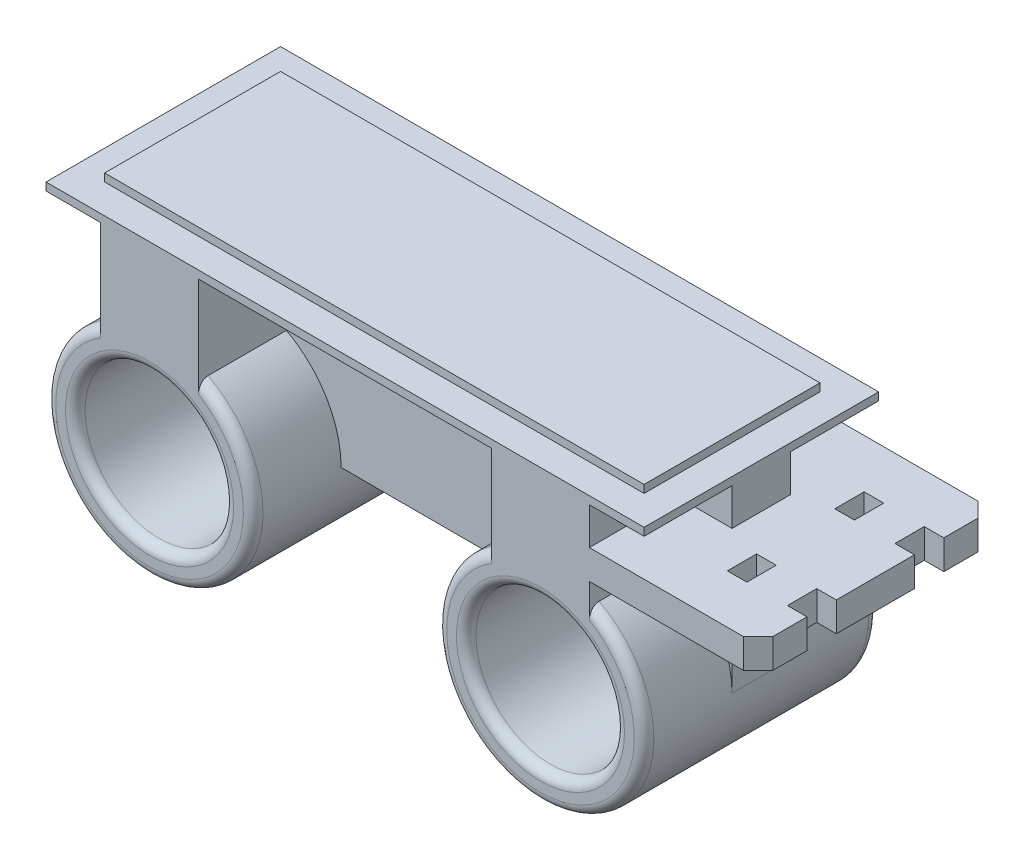
SolidWorks part; units mm, degrees
ref_plane "Plano frontal" through (0, 0, 0) normal (0, 0, 1) x (1, 0, 0)
ref_plane "Plano superior" through (0, 0, 0) normal (0, 1, 0) x (1, 0, 0)
ref_plane "Plano direito" through (0, 0, 0) normal (1, 0, 0) x (0, 0, -1)
sketch "Esboço1" plane through (0, 0, 0) normal (0, 0, 1) x (1, 0, 0)
  line L0 (-20, 0) -> (20, 0) construction
  circle A0 centre (-20, 0) radius 7.6
  circle A1 centre (-20, 0) radius 10.6
  circle A2 centre (20, 0) radius 10.6
  circle A3 centre (20, 0) radius 7.6
  point P2 (0, 0)
  dimension "D1" = 15.2
  dimension "D2" = 15.2
  dimension "D4" = 3
  dimension "D5" = 3
  dimension "D3" = 40
extrude "Ressalto-extrusão1" add sketch "Esboço1" along normal mid plane 24
fillet "Filete1" radius 1 4 edges at (-9.4, 0, -12) (-12.4, 0, -12) (-12.4, 0, 12) (-9.4, 0, 12)
fillet "Filete2" radius 1 4 edges at (27.6, 0, -12) (30.6, 0, -12) (30.6, 0, 12) (27.6, 0, 12)
sketch "Esboço2" plane through (0, 0, 0) normal (0, 0, 1) x (1, 0, 0)
  line L0 (-30.6, 0) -> (-30.6, 20)
  line L1 (-30.6, 20) -> (30.6, 20)
  line L2 (30.6, 0) -> (30.6, 20)
  line L3 (-9.4, 0) -> (9.4, 0)
  circle A0 centre (-20, 0) radius 10.6 construction
  circle A1 centre (20, 0) radius 10.6 construction
  arc A2 (-9.4, 0) -> (-30.6, 0) centre (-20, 0) ccw
  arc A3 (30.6, 0) -> (9.4, 0) centre (20, 0) ccw
  dimension "D1" = 20
extrude "Ressalto-extrusão2" add sketch "Esboço2" along normal mid plane 6
sketch "Esboço3" plane through (0, 0, 0) normal (0, 0, 1) x (1, 0, 0)
  line L0 (30.6, 0) -> (30.6, 20) construction
  line L1 (-30.6, 20) -> (30.6, 20)
  line L2 (-30.6, 20) -> (-30.6, 18.4)
  line L4 (30.6, 20) -> (30.6, 18.4)
  line L11 (30.6, 18.4) -> (25, 18.4)
  line L17 (15, 18.4) -> (-15, 18.4)
  line L29 (-25, 18.4) -> (-30.6, 18.4)
  line L30 (-25, 8.1951) -> (-25, 18.4)
  line L34 (-15, 8.1951) -> (-15, 18.4)
  line L38 (25, 8.1951) -> (25, 18.4)
  line L40 (15, 8.1951) -> (15, 18.4)
  circle A1 centre (20, 0) radius 9.6 construction
  circle A5 centre (-20, 0) radius 9.6 construction
  arc A9 (25, 8.1951) -> (15, 8.1951) centre (20, 0) ccw
  arc A10 (-15, 8.1951) -> (-25, 8.1951) centre (-20, 0) ccw
  point P7 (-20, 0)
  point P13 (20, 0)
  dimension "D1" = 1.6
extrude "Ressalto-extrusão3" add sketch "Esboço3" along normal mid plane 24
sketch "Esboço5" plane through (0, 20, 0) normal (0, 1, 0) x (1, 0, 0)
  line L0 (27.6, 9) -> (-27.6, 9)
  line L1 (-27.6, 9) -> (-27.6, -9)
  line L2 (-27.6, -9) -> (27.6, -9)
  line L3 (27.6, -9) -> (27.6, 9)
  line L4 (30.6, -12) -> (30.6, 12)
  line L5 (30.6, 12) -> (-30.6, 12)
  line L6 (-30.6, 12) -> (-30.6, -12)
  line L7 (-30.6, -12) -> (30.6, -12)
  line L8 (30.6, -12) -> (30.6, 12)
  line L9 (30.6, 12) -> (-30.6, 12)
  line L10 (-30.6, 12) -> (-30.6, -12)
  line L11 (-30.6, -12) -> (30.6, -12)
  dimension "D1" = 0
  dimension "D2" = 3
extrude "Corte-extrusão1" cut sketch "Esboço5" against normal blind 0.8
ref_plane "Plano1" through (42.27, 0, 0) normal (1, 0, 0) x (0, 0, -1)
sketch "Esboço6" plane through (42.27, 0, 0) normal (1, 0, 0) x (0, 0, -1)
  line L0 (-12, 11.6) -> (12, 11.6)
  line L2 (12, 14.6) -> (-12, 14.6)
  line L3 (-12, 8.1951) -> (-12, 18.4) construction
  line L4 (-12, 14.6) -> (-12, 11.6)
  line L5 (12, 14.6) -> (12, 11.6)
  line L7 (-13.3233, 11.2) -> (13.2154, 11.2) construction
  dimension "D2" = 3
  dimension "D3" = 0.4
extrude "Ressalto-extrusão4" add sketch "Esboço6" against normal blind 22
sketch "Esboço9" plane through (0, 14.6, 0) normal (0, 1, 0) x (1, 0, 0)
  line L0 (40.27, 20.1519) -> (40.27, -18.8479) construction
  line L1 (40.27, -18.8479) -> (36.12, -18.8479) construction
  line L2 (36.12, -18.8479) -> (36.12, 22.4041) construction
  line L3 (42.27, 12) -> (42.27, -12) construction
  line L4 (42.27, 7) -> (40.27, 7)
  line L7 (40.27, 7) -> (40.27, 4)
  line L8 (40.27, 4) -> (42.27, 4)
  line L9 (42.27, -4) -> (40.27, -4)
  line L10 (40.27, -4) -> (40.27, -7)
  line L11 (40.27, -7) -> (42.27, -7)
  line L12 (25, 12) -> (42.27, 12) construction
  line L13 (25, -12) -> (42.27, -12) construction
  line L14 (42.27, -7) -> (42.27, -4)
  line L15 (42.27, 7) -> (42.27, 4)
  line L16 (34.12, 7) -> (36.12, 7)
  line L17 (36.12, 7) -> (36.12, 4)
  line L18 (36.12, 4) -> (34.12, 4)
  line L19 (34.12, 4) -> (34.12, 7)
  line L21 (34.12, -4) -> (36.12, -4)
  line L22 (34.12, -4) -> (34.12, -7)
  line L23 (34.12, -7) -> (36.12, -7)
  line L24 (36.12, -4) -> (36.12, -7)
  dimension "D1" = 2
  dimension "D2" = 4.15
  dimension "D3" = 3
  dimension "D4" = 3
  dimension "D5" = 5
  dimension "D6" = 5
  dimension "D7" = 2
  dimension "D8" = 2
extrude "Corte-extrusão2" cut sketch "Esboço9" against normal blind 10
chamfer "Chanfro1" distance 1.5 angle 45 2 edges at (42.27, 13.1, -12) (42.27, 13.1, 12)
sketch "Esboço10" plane through (0, 19.2, 0) normal (0, 1, 0) x (1, 0, 0)
  line L0 (-30.6, 0) -> (30.6, 0) construction
  line L1 (-30.6, 12) -> (-30.6, -12) construction
  line L2 (30.6, -12) -> (30.6, 12) construction
  line L4 (30.6, 12) -> (-30.6, 12) construction
  line L5 (0, 12) -> (0, -12) construction
  line L6 (-30.6, -12) -> (30.6, -12) construction
